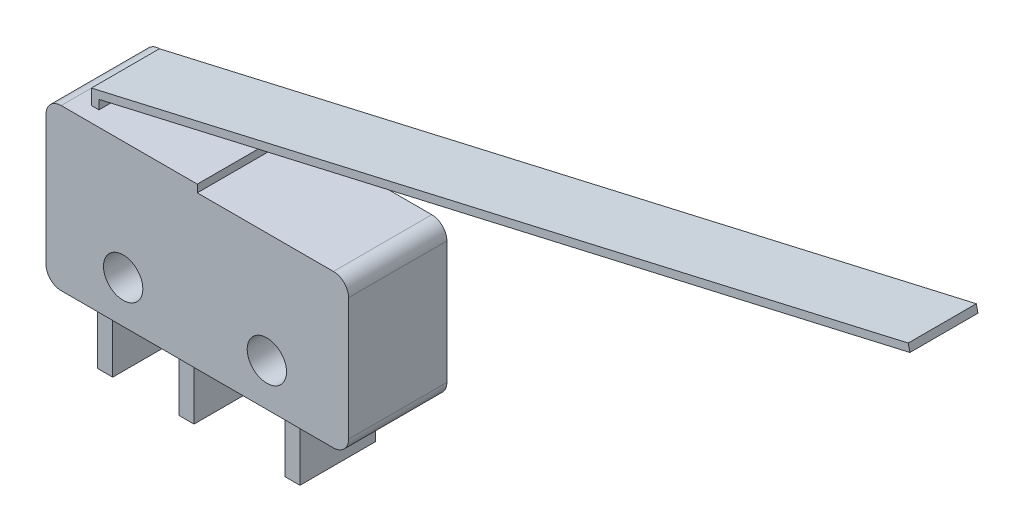
SolidWorks part; units mm, degrees
ref_plane "Front Plane" through (0, 0, 0) normal (0, 0, 1) x (1, 0, 0)
ref_plane "Top Plane" through (0, 0, 0) normal (0, 1, 0) x (1, 0, 0)
ref_plane "Right Plane" through (0, 0, 0) normal (1, 0, 0) x (0, 0, -1)
sketch "Sketch1" plane through (0, 0, 0) normal (0, 0, 1) x (1, 0, 0)
  line L0 (10, 10.6) -> (10, 10.1)
  line L1 (0, 0) -> (20, 0)
  line L2 (0, 0) -> (0, 10.6)
  line L3 (0, 10.6) -> (10, 10.6)
  line L4 (20, 0) -> (20, 10.1)
  line L5 (10, 10.1) -> (20, 10.1)
  point P1 (0, 0)
  point P7 (10, 0)
  dimension "D1" = 20
  dimension "D2" = 10.6
  dimension "D3" = 10.1
extrude "Boss-Extrude1" add sketch "Sketch1" along normal blind 6.5
fillet "Fillet1" radius 1 4 edges at (0, 10.6, 3.25) (0, 0, 3.25) (20, 0, 3.25) (20, 10.1, 3.25)
hole_wizard "M2 Clearance Hole1" positions "Sketch4" profile "Sketch3" hole size "M2" standard "ANSI Metric" end condition through all
sketch "Sketch4" plane through (0, 0, 6.5) normal (0, 0, 1) x (1, 0, 0)
  line L0 (1, 0) -> (19, 0) construction
  line L1 (0, 9.6) -> (0, 1) construction
  point P0 (5.1, 2.8)
  point P2 (14.6, 2.8)
  point P9 (5.1, 3.1569)
  dimension "D1" = 9.5
  dimension "D2" = 2.8
  dimension "D3" = 5.1
sketch "Sketch3" plane through (5.1, 2.8, 6.5) normal (1, 0, 0) x (0, -1, 0)
  line L0 (0, 0) -> (0, 6.5)
  line L1 (0, 6.5) -> (1.3, 6.5)
  line L2 (1.3, 6.5) -> (1.3, 0)
  line L5 (1.3, 0) -> (0, 0)
  line L11 (0, -6.35) -> (0, 107.95) construction
  dimension "Thru Hole Dia." = 2.6
  dimension "Thru Hole Depth" = 6.5
sketch "Sketch5" plane through (0, 0, 6.5) normal (0, 0, 1) x (1, 0, 0)
  line L0 (2, 11.6) -> (2, 10.6)
  line L1 (2, 10.6) -> (2.5, 10.6)
  line L2 (2.5, 10.6) -> (2.5, 11.2018)
  line L3 (2.5, 11.2018) -> (56.1045, 23.5127)
  line L4 (56.1045, 23.5127) -> (55.9926, 24)
  line L5 (55.9926, 24) -> (2, 11.6)
  line L7 (10, 10.6) -> (1, 10.6) construction
  line L8 (0, 9.6) -> (0, 1) construction
  dimension "D1" = 0.5
  dimension "D2" = 55
  dimension "D3" = 13.4
  dimension "D4" = 2
  dimension "D5" = 1
extrude "Boss-Extrude2" add sketch "Sketch5" against normal offset from surface (4.5 mm away) 1 from offset 1 up to face at (6.4, 2.8, 0) offset against normal yes
sketch "Sketch6" plane through (0, 0, 0) normal (0, -1, 0) x (1, 0, 0)
  line L0 (1, 3.25) -> (2.659, 3.25) construction
  line L1 (2.659, 5.75) -> (3.659, 5.75)
  line L2 (2.659, 5.75) -> (2.659, 0.75)
  line L3 (2.659, 0.75) -> (3.659, 0.75)
  line L4 (3.659, 5.75) -> (3.659, 0.75)
  line L5 (8.0314, 5.75) -> (9.0314, 5.75)
  line L6 (8.0314, 5.75) -> (8.0314, 0.75)
  line L7 (8.0314, 0.75) -> (9.0314, 0.75)
  line L8 (9.0314, 5.75) -> (9.0314, 0.75)
  line L9 (15.0359, 5.75) -> (16.0359, 5.75)
  line L10 (15.0359, 5.75) -> (15.0359, 0.75)
  line L11 (15.0359, 0.75) -> (16.0359, 0.75)
  line L12 (16.0359, 5.75) -> (16.0359, 0.75)
  line L13 (1, 6.5) -> (1, 0) construction
  dimension "D1" = 1
  dimension "D2" = 5
extrude "Boss-Extrude3" add sketch "Sketch6" along normal blind 4
